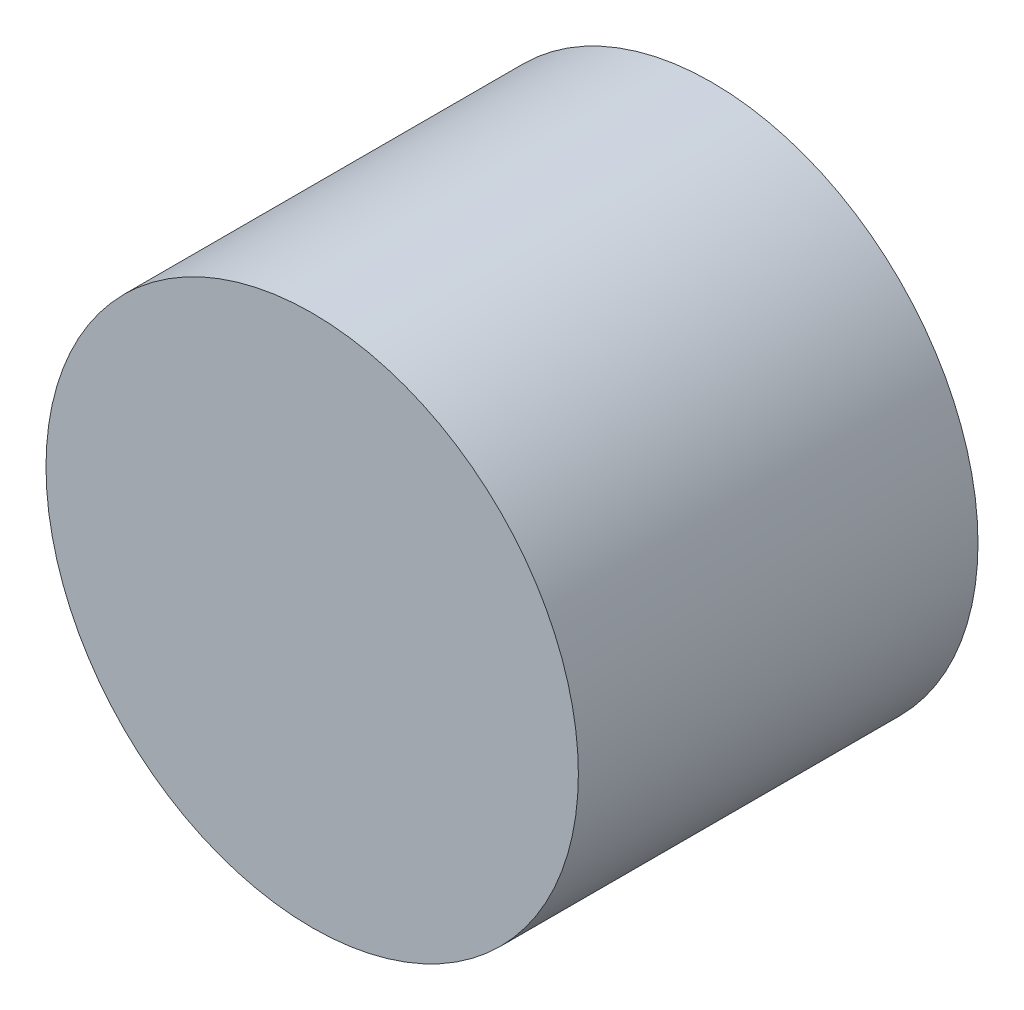
SolidWorks part; units mm, degrees
ref_plane "Front Plane" through (0, 0, 0) normal (0, 0, 1) x (1, 0, 0)
ref_plane "Top Plane" through (0, 0, 0) normal (0, 1, 0) x (1, 0, 0)
ref_plane "Right Plane" through (0, 0, 0) normal (1, 0, 0) x (0, 0, -1)
sketch "Sketch1" plane through (0, 0, 0) normal (0, 0, 1) x (1, 0, 0)
  circle A0 centre (-4.913, 6.281) radius 9.2432
  dimension "D1" = 9.2432
extrude "Boss-Extrude1" add sketch "Sketch1" along normal blind 13.8772
